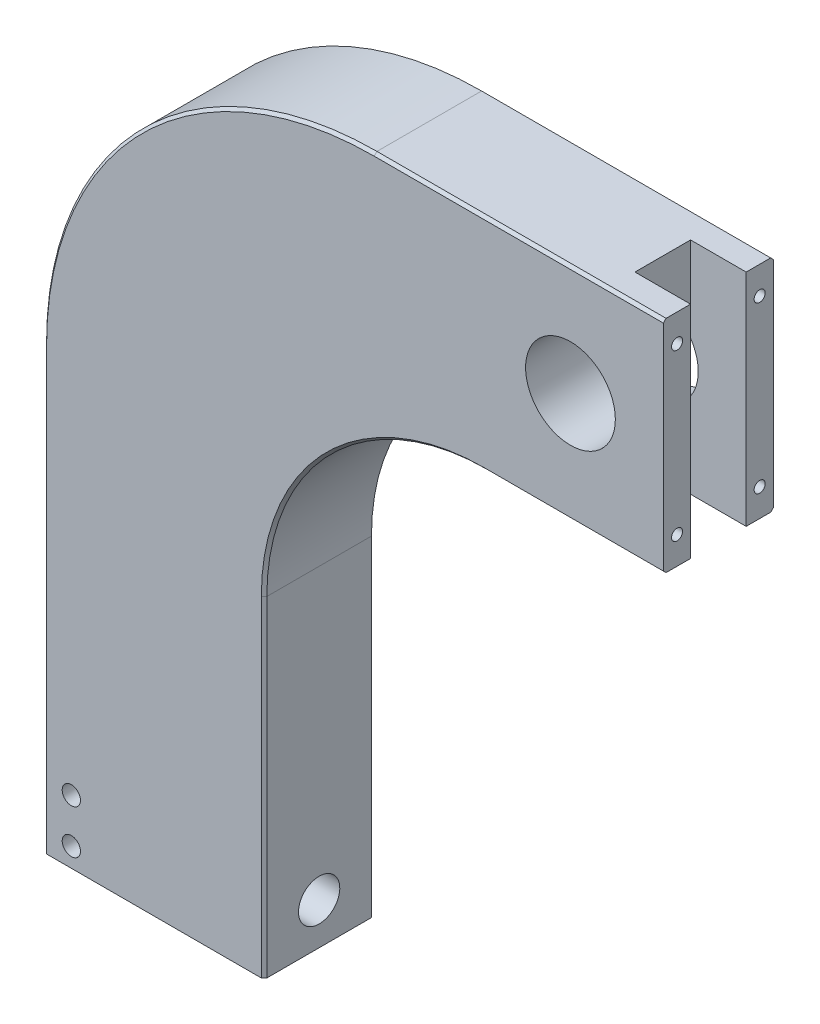
SolidWorks part; units mm, degrees
ref_plane "Front Plane" through (0, 0, 0) normal (0, 0, 1) x (1, 0, 0)
ref_plane "Top Plane" through (0, 0, 0) normal (0, 1, 0) x (1, 0, 0)
ref_plane "Right Plane" through (0, 0, 0) normal (1, 0, 0) x (0, 0, -1)
sketch "Sketch1" plane through (0, 0, 0) normal (0, 0, 1) x (1, 0, 0)
  line L0 (0, 0) -> (0, 203.2)
  line L1 (152.4, 355.6) -> (285.75, 355.6)
  line L2 (285.75, 355.6) -> (285.75, 254)
  line L3 (285.75, 254) -> (203.2, 254)
  line L4 (101.6, 152.4) -> (101.6, 0)
  line L5 (101.6, 0) -> (0, 0)
  line L6 (227.2802, 304.8) -> (285.75, 304.8) construction
  arc A0 (152.4, 355.6) -> (0, 203.2) centre (152.4, 203.2) ccw
  arc A1 (203.2, 254) -> (101.6, 152.4) centre (203.2, 152.4) ccw
  circle A2 centre (242.9256, 304.8) radius 20.701
  point P9 (0, 355.6)
  dimension "D5" = 152.4
  dimension "D6" = 101.6
  dimension "D7" = 41.402
  dimension "D1" = 355.6
  dimension "D2" = 285.75
  dimension "D3" = 101.6
  dimension "D4" = 101.6
  dimension "D8" = 42.8244
extrude "Boss-Extrude1" add sketch "Sketch1" along normal mid plane 50.8
sketch "Sketch2" plane through (285.75, 0, 0) normal (1, 0, 0) x (0, 0, -1)
  line L0 (0, 355.6) -> (0, 254) construction
  line L1 (-25.4, 355.6) -> (25.4, 355.6) construction
  line L2 (-25.4, 254) -> (25.4, 254) construction
  line L3 (25.4, 254) -> (25.4, 355.6) construction
  line L4 (-12.827, 355.6) -> (12.827, 355.6)
  line L5 (-12.827, 355.6) -> (-12.827, 254)
  line L6 (-12.827, 254) -> (12.827, 254)
  line L7 (12.827, 355.6) -> (12.827, 254)
  dimension "D1" = 25.654
  dimension "D2" = 12.573
extrude "Cut-Extrude1" cut sketch "Sketch2" against normal blind 25.654
hole_wizard "1/4-20 Tapped Hole1" positions "Sketch4" profile "Sketch5" tap size "1/4-20" standard "ANSI Inch"
sketch "Sketch4" plane through (285.75, 0, 0) normal (1, 0, 0) x (0, 0, -1)
  line L0 (25.4, 254) -> (25.4, 355.6) construction
  line L1 (12.827, 355.6) -> (25.4, 355.6) construction
  line L2 (-25.4, 254) -> (-25.4, 355.6) construction
  line L3 (-25.4, 355.6) -> (-12.827, 355.6) construction
  line L4 (-25.4, 254) -> (25.4, 254) construction
  point P0 (19.05, 342.9)
  point P2 (-19.05, 342.9)
  point P13 (-19.05, 266.7)
  point P15 (19.05, 266.7)
  dimension "D1" = 6.35
  dimension "D2" = 12.7
  dimension "D3" = 6.35
  dimension "D4" = 12.7
  dimension "D5" = 6.35
  dimension "D6" = 6.35
  dimension "D7" = 12.7
  dimension "D8" = 12.7
sketch "Sketch5" plane through (285.75, 342.9, -19.05) normal (0, 1, 0) x (0, 0, -1)
  line L0 (0, 0) -> (0, 26.9338)
  line L1 (0, 26.9338) -> (2.5527, 25.4)
  line L2 (2.5527, 25.4) -> (2.5527, 0)
  line L5 (2.5527, 0) -> (0, 0)
  line L10 (0, 26.9338) -> (-2.5527, 25.4) construction
  line L11 (0, -6.35) -> (0, 107.95) construction
  dimension "Tap Drill Dia." = 5.1054
  dimension "Tap Drill Depth" = 25.4
  dimension "Drill Angle" = 118
cosmetic thread "Hole Thread1" parameters "D1"=19.05, "D2"=6.35
cosmetic thread "Hole Thread2" parameters "D1"=19.05, "D2"=6.35
cosmetic thread "Hole Thread3" parameters "D1"=19.05, "D2"=6.35
cosmetic thread "Hole Thread4" parameters "D1"=19.05, "D2"=6.35
hole_wizard "3/8-24 Tapped Hole1" positions "Sketch8" profile "Sketch9" tap size "3/8-24" standard "ANSI Inch" end condition through all
sketch "Sketch8" plane through (0, 0, 25.4) normal (0, 0, 1) x (1, 0, 0)
  line L0 (101.6, 0) -> (101.6, 152.4) construction
  line L1 (0, 0) -> (101.6, 0) construction
  point P0 (12.7, 29.21)
  point P2 (12.7, 8.89)
  point P3 (0, 0)
  point P4 (0, 0)
  dimension "D1" = 88.9
  dimension "D2" = 8.89
  dimension "D3" = 20.32
sketch "Sketch9" plane through (12.7, 29.21, 25.4) normal (1, 0, 0) x (0, -1, 0)
  line L0 (0, 0) -> (0, 50.8)
  line L1 (0, 50.8) -> (4.2164, 50.8)
  line L2 (4.2164, 50.8) -> (4.2164, 0)
  line L5 (4.2164, 0) -> (0, 0)
  line L11 (0, -6.35) -> (0, 107.95) construction
  dimension "Thru Tap Drill Dia." = 8.4328
  dimension "Thru Tap Drill Depth" = 50.8
cosmetic thread "Hole Thread5" parameters "D2"=9.525
cosmetic thread "Hole Thread6" parameters "D2"=9.525
sketch "Sketch10" plane through (101.6, 0, 0) normal (1, 0, 0) x (0, 0, -1)
  line L0 (0, 19.05) -> (0, 0) construction
  line L1 (-25.4, 0) -> (25.4, 0) construction
  circle A0 centre (0, 19.05) radius 9.525
  dimension "D1" = 19.05
  dimension "D2" = 19.05
extrude "Cut-Extrude2" cut sketch "Sketch10" against normal blind 19.05
chamfer "Chamfer1" distance 1.27 angle 45 12 edges at (219.075, 355.6, -25.4) (44.6369, 310.9631, -25.4) (0, 101.6, -25.4) (0, 101.6, 25.4) (44.6369, 310.9631, 25.4) (219.075, 355.6, 25.4) (244.475, 254, -25.4) (131.358, 224.242, -25.4) (101.6, 76.2, -25.4) (244.475, 254, 25.4) (131.358, 224.242, 25.4) (101.6, 76.2, 25.4)
